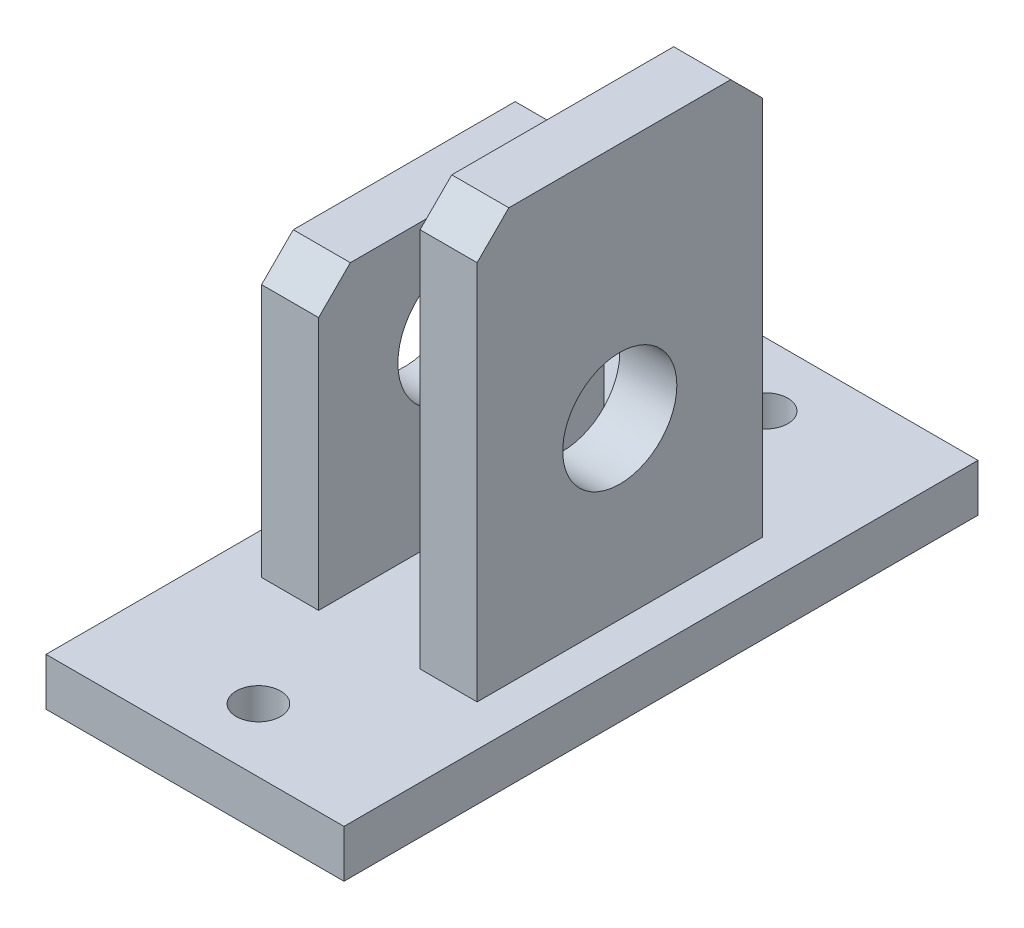
SolidWorks part; units mm, degrees
material "Structural Steel"
ref_plane "Piano frontale" through (0, 0, 0) normal (0, 0, 1) x (1, 0, 0)
ref_plane "Piano superiore" through (0, 0, 0) normal (0, 1, 0) x (1, 0, 0)
ref_plane "Piano destro" through (0, 0, 0) normal (1, 0, 0) x (0, 0, -1)
sketch "Schizzo1" plane through (0, 0, 0) normal (0, 1, 0) x (1, 0, 0)
  line L1 (0, 0) -> (94, 0)
  line L2 (0, 0) -> (0, 200)
  line L3 (0, 200) -> (94, 200)
  line L4 (94, 0) -> (94, 200)
  dimension "D1" = 94
  dimension "D2" = 200
extrude "Estrusione1" add sketch "Schizzo1" along normal blind 15
sketch "Schizzo2" plane through (0, 15, 0) normal (0, 1, 0) x (1, 0, 0)
  line L0 (47, 200) -> (47, -10.7714) construction
  line L1 (94, 200) -> (0, 200) construction
  line L2 (0, 100) -> (118.1935, 100) construction
  line L3 (0, 200) -> (0, 0) construction
  line L4 (81, 55) -> (81, 145)
  line L5 (63, 145) -> (81, 145)
  line L6 (31, 55) -> (31, 145)
  line L7 (31, 145) -> (13, 145)
  line L8 (13, 55) -> (13, 145)
  line L9 (63, 55) -> (63, 145)
  line L10 (31, 55) -> (13, 55)
  line L11 (63, 55) -> (81, 55)
  point P19 (63, 100)
  point P20 (13, 100)
  point P21 (31, 100)
  point P22 (81, 100)
  dimension "D3" = 16
  dimension "D4" = 18
  dimension "D5" = 45
extrude "Estrusione2" add sketch "Schizzo2" along normal blind 90
sketch "Schizzo3" plane through (0, 15, 0) normal (0, 1, 0) x (1, 0, 0)
  line L0 (47, 200) -> (47, -9.6005) construction
  line L1 (94, 200) -> (0, 200) construction
  line L2 (0, 100) -> (102.737, 100) construction
  line L3 (0, 200) -> (0, 0) construction
  circle A0 centre (47, 180) radius 7
  circle A1 centre (47, 20) radius 7
  dimension "D1" = 14
  dimension "D2" = 80
extrude "Estrusione3" cut sketch "Schizzo3" against normal blind 90
sketch "Schizzo4" plane through (81, 0, 0) normal (1, 0, 0) x (0, 0, -1)
  line L0 (100, 105) -> (100, 53.9477) construction
  line L1 (55, 105) -> (145, 105) construction
  line L2 (0, 15) -> (200, 15) construction
  circle A0 centre (100, 70) radius 18
  dimension "D1" = 36
  dimension "D2" = 55
extrude "Estrusione4" cut sketch "Schizzo4" against normal through all
sketch "Schizzo5" plane through (13, 0, 0) normal (-1, 0, 0) x (0, 0, 1)
  circle A0 centre (-100, 70) radius 20
  dimension "D1" = 40
extrude "Estrusione5" cut sketch "Schizzo5" against normal blind 20
sketch "Schizzo7" plane through (0, 105, 0) normal (0, 1, 0) x (1, 0, 0)
  line L1 (63, 145) -> (81, 145)
  line L2 (63, 145) -> (63, 55)
  line L3 (63, 55) -> (81, 55)
  line L4 (81, 145) -> (81, 55)
extrude "Estrusione6" add sketch "Schizzo7" along normal blind 40
chamfer "Smusso1" distance 10 angle 45 4 edges at (22, 105, -145) (72, 145, -145) (72, 145, -55) (22, 105, -55)
